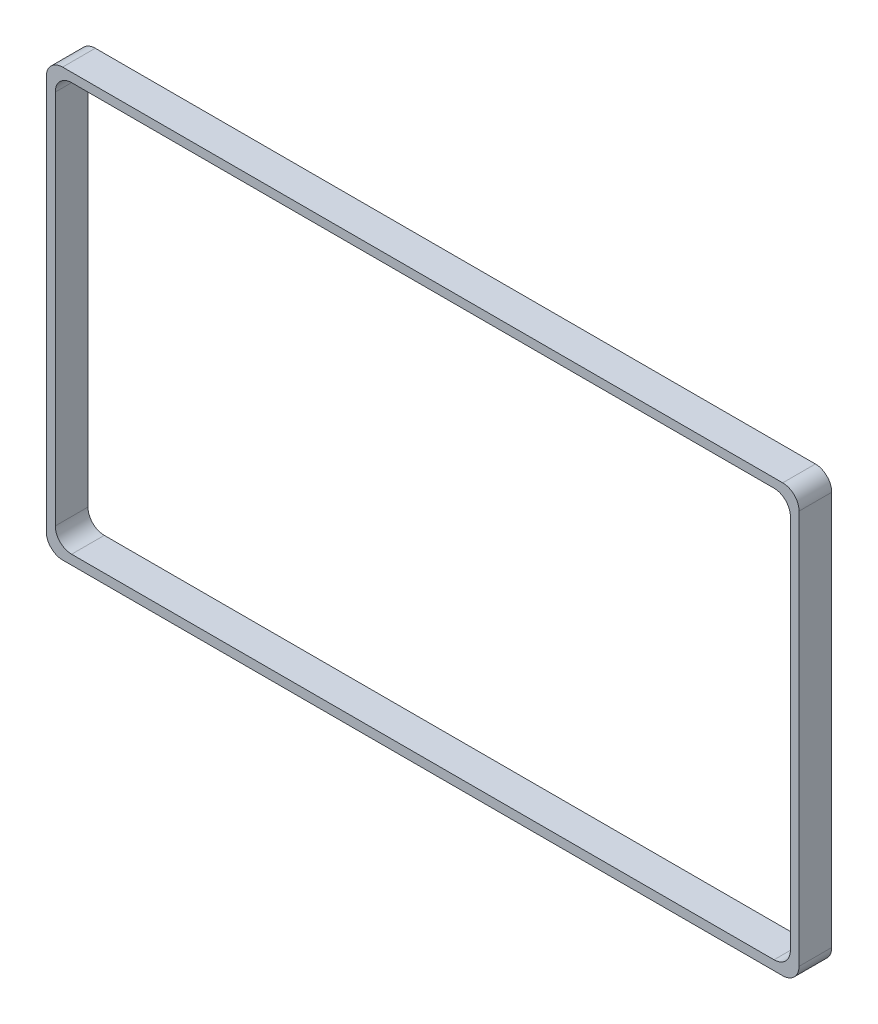
SolidWorks part; units mm, degrees
material "1060 合金"
ref_plane "前视基准面" through (0, 0, 0) normal (0, 0, 1) x (1, 0, 0)
ref_plane "上视基准面" through (0, 0, 0) normal (0, 1, 0) x (1, 0, 0)
ref_plane "右视基准面" through (0, 0, 0) normal (1, 0, 0) x (0, 0, -1)
sketch "草图2" plane through (0, 0, 0) normal (0, 0, 1) x (1, 0, 0)
  line L0 (-3.3667, 2.5583) -> (-4.1916, 3.3833)
  line L1 (-3.3667, 2.5583) -> (1.1333, 2.5583)
  line L2 (-3.3667, 2.5583) -> (-3.3667, 0.0583)
  line L3 (-3.3667, 0.0583) -> (1.1333, 0.0583)
  line L4 (1.1333, 2.5583) -> (1.1333, 0.0583)
  line L6 (-3.4216, 2.6133) -> (1.1864, 2.6133)
  line L7 (-3.4216, 2.6133) -> (-3.4216, 0)
  line L8 (-3.4216, 0) -> (1.1864, 0)
  line L9 (1.1864, 2.6133) -> (1.1864, 0)
  dimension "D1" = 4.5
  dimension "D2" = 2.5
extrude "凸台-拉伸1" add sketch "草图2" along normal blind 0.2
fillet "圆角1" radius 0.1 8 edges at (1.1333, 0.0583, 0.1) (1.1864, 0, 0.1) (1.1864, 2.6133, 0.1) (1.1333, 2.5583, 0.1) (-3.3667, 0.0583, 0.1) (-3.4216, 0, 0.1) (-3.4216, 2.6133, 0.1) (-3.3667, 2.5583, 0.1)
